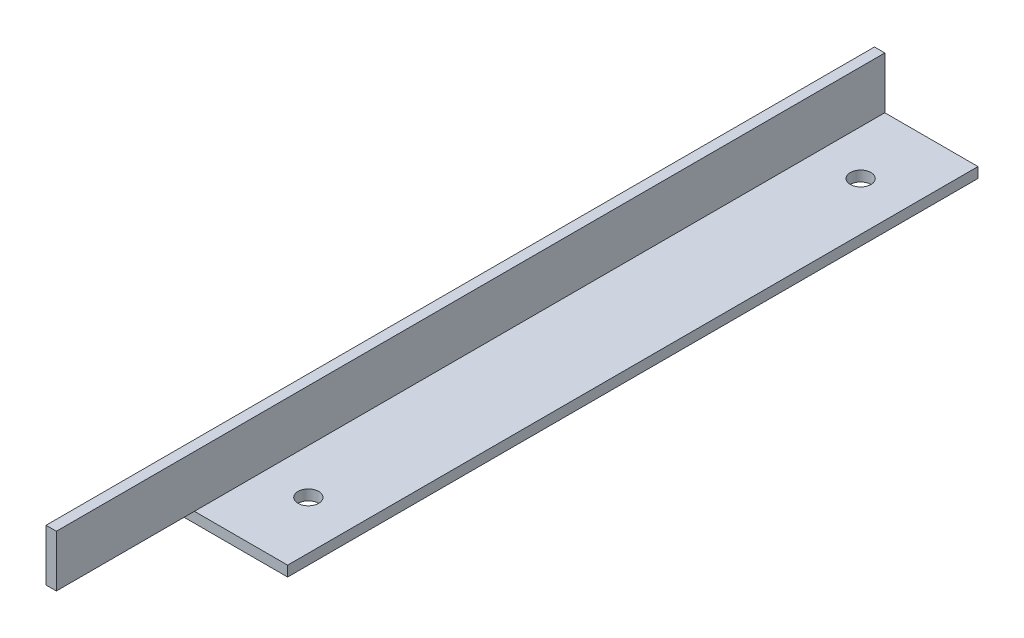
SolidWorks part; units mm, degrees
ref_plane "Plan de face" through (0, 0, 0) normal (0, 0, 1) x (1, 0, 0)
ref_plane "Plan de dessus" through (0, 0, 0) normal (0, 1, 0) x (1, 0, 0)
ref_plane "Plan de droite" through (0, 0, 0) normal (1, 0, 0) x (0, 0, -1)
sketch "Esquisse1" plane through (0, 0, 0) normal (0, 0, 1) x (1, 0, 0)
  line L0 (-18.3407, -0.5451) -> (-18.3407, -9.5451)
  line L1 (-18.3407, -9.5451) -> (-3.3407, -9.5451)
  line L2 (-3.3407, -9.5451) -> (-3.3407, -8.0451)
  line L3 (-3.3407, -8.0451) -> (-16.8407, -8.0451)
  line L4 (-16.8407, -8.0451) -> (-16.8407, -0.5451)
  line L5 (-16.8407, -0.5451) -> (-18.3407, -0.5451)
  dimension "D1" = 1.5
  dimension "D2" = 1.5
  dimension "D3" = 15
  dimension "D4" = 9
extrude "Extrusion1" add sketch "Esquisse1" along normal blind 100
sketch "Esquisse2" plane through (0, -8.0451, 0) normal (0, 1, 0) x (-1, 0, 0)
  line L0 (10.3407, 10) -> (10.3407, 90) construction
  line L1 (3.3407, 100) -> (16.8407, 100) construction
  line L2 (3.3407, 0) -> (16.8407, 0) construction
  line L3 (3.3407, 100) -> (3.3407, 0) construction
  circle A0 centre (10.3407, 90) radius 1.5
  circle A1 centre (10.3407, 10) radius 1.5
  dimension "D3" = 7
  dimension "D1" = 10
  dimension "D2" = 10
extrude "Extrusion2" cut sketch "Esquisse2" against normal blind 120
sketch "Esquisse3" plane through (0, 0, 100) normal (0, 0, 1) x (1, 0, 0)
  line L1 (-18.3407, -0.5451) -> (-16.8407, -0.5451)
  line L2 (-18.3407, -0.5451) -> (-18.3407, -8.0451)
  line L3 (-18.3407, -8.0451) -> (-16.8407, -8.0451)
  line L4 (-16.8407, -0.5451) -> (-16.8407, -8.0451)
extrude "Extrusion3" add sketch "Esquisse3" along normal blind 20
